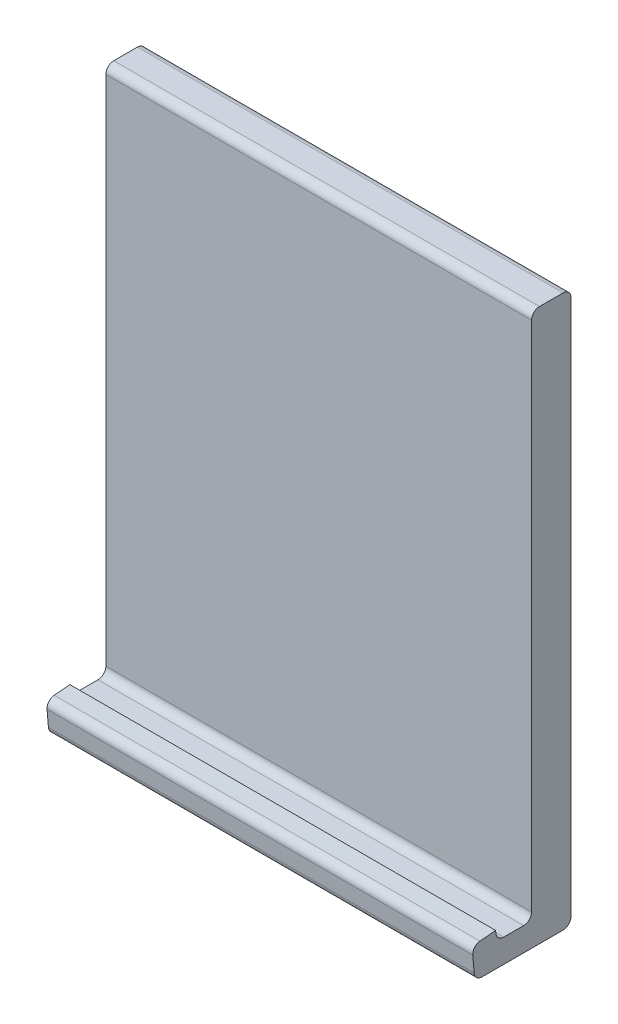
SolidWorks part; units mm, degrees
ref_plane "Front Plane" through (0, 0, 0) normal (0, 0, 1) x (1, 0, 0)
ref_plane "Top Plane" through (0, 0, 0) normal (0, 1, 0) x (1, 0, 0)
ref_plane "Right Plane" through (0, 0, 0) normal (1, 0, 0) x (0, 0, -1)
sketch "Sketch2" plane through (0, 0, 0) normal (0, 0, 1) x (1, 0, 0)
  line L1 (0, 70) -> (54, 70)
  line L2 (0, 70) -> (0, 0)
  line L3 (0, 0) -> (54, 0)
  line L4 (54, 70) -> (54, 0)
  dimension "D1" = 70
  dimension "D2" = 54
extrude "Boss-Extrude1" add sketch "Sketch2" against normal blind 5
sketch "Sketch6" plane through (0, 0, 0) normal (1, 0, 0) x (0, 0, -1)
  line L0 (5, 0) -> (5, 3)
  line L1 (5, 0) -> (5, 70) construction
  line L2 (5, 3) -> (-4.451, 3)
  line L3 (-4.451, 3) -> (-4.56, 4.2462)
  line L4 (-4.56, 4.2462) -> (-7.5486, 3.9848)
  line L5 (5, 0) -> (-7.2, 0)
  line L6 (-7.2, 0) -> (-7.5486, 3.9848)
  line L7 (0, 0) -> (0, 70) construction
  dimension "D1" = 3
  dimension "D2" = 4
  dimension "D3" = 12.2
  dimension "D4" = 90
  dimension "D5" = 3
  dimension "D6" = 95
extrude "Boss-Extrude3" add sketch "Sketch6" along normal through all contours L4 L6 L5 L0 L2 L3
fillet "Fillet1" radius 1 7 edges at (27, 70, -5) (27, 70, 0) (27, 0, -5) (27, 0, 7.2) (27, 3.9848, 7.5486) (27, 3, 4.451) (27, 3, 0)
